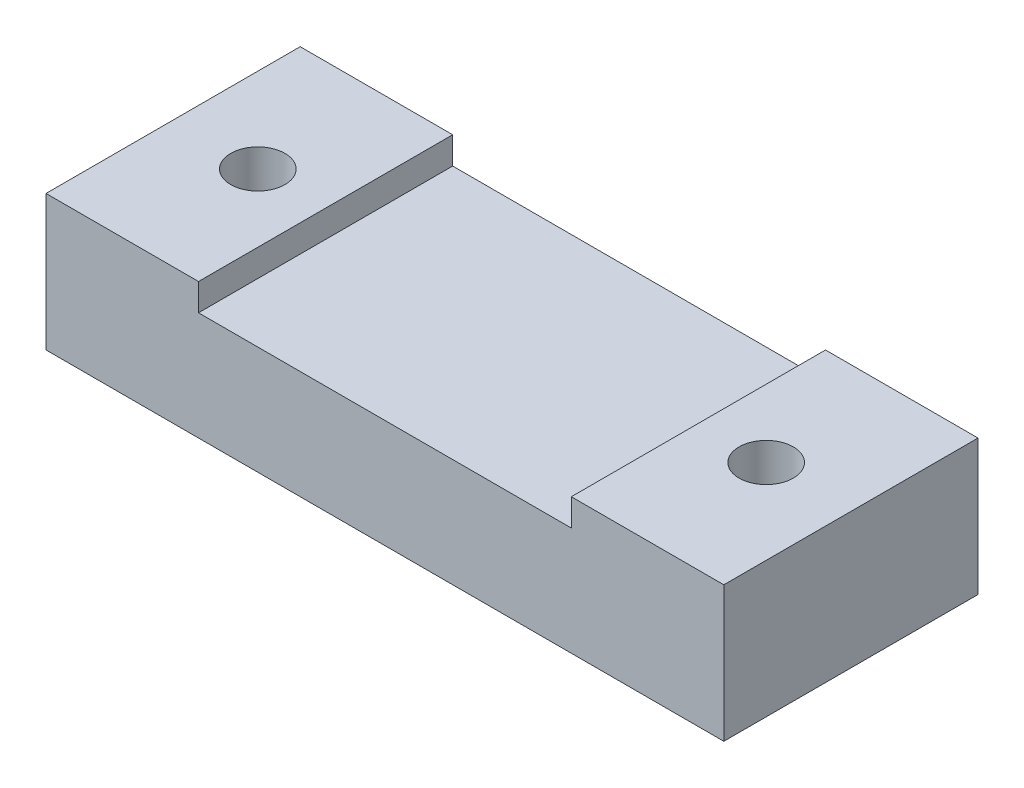
SolidWorks part; units mm, degrees
ref_plane "Front Plane" through (0, 0, 0) normal (0, 0, 1) x (1, 0, 0)
ref_plane "Top Plane" through (0, 0, 0) normal (0, 1, 0) x (1, 0, 0)
ref_plane "Right Plane" through (0, 0, 0) normal (1, 0, 0) x (0, 0, -1)
sketch "Sketch1" plane through (0, 0, 0) normal (0, 1, 0) x (1, 0, 0)
  line L1 (-20, 7.5) -> (20, 7.5)
  line L2 (-20, 7.5) -> (-20, -7.5)
  line L3 (-20, -7.5) -> (20, -7.5)
  line L4 (20, 7.5) -> (20, -7.5)
  line L5 (-20, 7.5) -> (20, -7.5) construction
  line L6 (-20, -7.5) -> (20, 7.5) construction
  point P0 (0, 0)
  dimension "D1" = 40
  dimension "D2" = 15
extrude "Boss-Extrude1" add sketch "Sketch1" along normal blind 8
sketch "Sketch2" plane through (0, 8, 0) normal (0, 1, 0) x (1, 0, 0)
  line L0 (-15, 0) -> (15, 0) construction
  line L2 (-20, -7.5) -> (20, -7.5) construction
  circle A0 centre (-15, 0) radius 1.6
  circle A1 centre (15, 0) radius 1.6
  dimension "D2" = 3.2
  dimension "D1" = 30
  dimension "D3" = 7.5
  dimension "D4" = 15
extrude "Cut-Extrude1" cut sketch "Sketch2" against normal through all
sketch "Sketch3" plane through (0, 8, 0) normal (0, 1, 0) x (1, 0, 0)
  line L0 (-20, -7.5) -> (20, -7.5) construction
  line L1 (-11, 7.5) -> (11, 7.5)
  line L2 (-11, 7.5) -> (-11, -7.5)
  line L3 (-11, -7.5) -> (11, -7.5)
  line L4 (11, 7.5) -> (11, -7.5)
  line L5 (-11, 7.5) -> (11, -7.5) construction
  line L6 (-11, -7.5) -> (11, 7.5) construction
  point P0 (0, 0)
  dimension "D1" = 22
extrude "Cut-Extrude2" cut sketch "Sketch3" against normal blind 1.6
sketch "Sketch4" plane through (0, 0, 0) normal (0, -1, 0) x (1, 0, 0)
  line L0 (0, 0) -> (0, 7.5) construction
  line L1 (-12, 1.7321) -> (-15, 3.4641)
  line L2 (-15, 3.4641) -> (-18, 1.7321)
  line L3 (-18, 1.7321) -> (-18, -1.7321)
  line L4 (-18, -1.7321) -> (-15, -3.4641)
  line L5 (-15, -3.4641) -> (-12, -1.7321)
  line L6 (-12, -1.7321) -> (-12, 1.7321)
  line L7 (-20, 7.5) -> (20, 7.5) construction
  line L8 (12, -1.7321) -> (12, 1.7321)
  line L9 (15, -3.4641) -> (12, -1.7321)
  line L10 (18, -1.7321) -> (15, -3.4641)
  line L11 (18, 1.7321) -> (18, -1.7321)
  line L12 (15, 3.4641) -> (18, 1.7321)
  line L13 (12, 1.7321) -> (15, 3.4641)
  circle A0 centre (-15, 0) radius 3 construction
  dimension "D1" = 6
extrude "Cut-Extrude3" cut sketch "Sketch4" against normal blind 3
